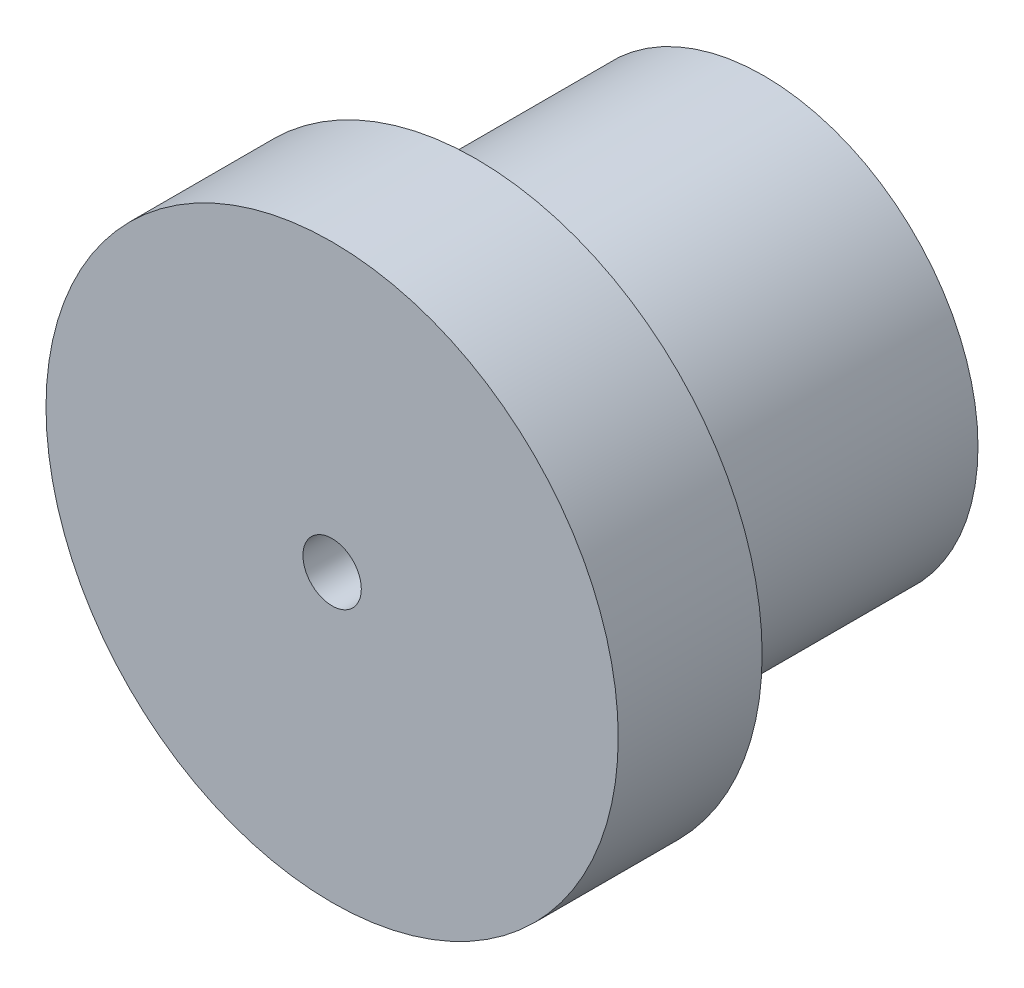
SolidWorks part; units mm, degrees
ref_plane "Front" through (0, 0, 0) normal (0, 0, 1) x (1, 0, 0)
ref_plane "Top" through (0, 0, 0) normal (0, 1, 0) x (1, 0, 0)
ref_plane "Right" through (0, 0, 0) normal (1, 0, 0) x (0, 0, -1)
sketch "Sketch1" plane through (0, 0, 0) normal (0, 0, 1) x (1, 0, 0)
  circle A0 centre (0, 0) radius 25.25
  circle A3 centre (0, 0) radius 25.4 construction
  dimension "D1" = 50.8
  dimension "D2" = 0.15
extrude "Boss-Extrude1" add sketch "Sketch1" against normal up to surface (12.7 mm away)
sketch "Sketch2" plane through (0, 0, -12.7) normal (0, 0, -1) x (-1, 0, 0)
  circle A0 centre (0, 0) radius 18.9
  circle A3 centre (0, 0) radius 19.05 construction
  dimension "D1" = 38.1
  dimension "D2" = 0.15
extrude "Boss-Extrude2" add sketch "Sketch2" along normal up to surface (25.4 mm away)
sketch "Sketch3" plane through (0, 0, -38.1) normal (0, 0, -1) x (-1, 0, 0)
  circle A0 centre (0, 0) radius 4.5
  dimension "D1" = 9
extrude "Cut-Extrude1" cut sketch "Sketch3" against normal blind 13
sketch "Sketch4" plane through (0, 0, 0) normal (0, 0, 1) x (1, 0, 0)
  line L0 (-2.24, 1.27) -> (2.24, 1.27)
  arc A0 (-2.24, 1.27) -> (2.24, 1.27) centre (0, 0) ccw
  arc A1 (2.24, 1.27) -> (-2.24, 1.27) centre (0, 0) ccw construction
  dimension "D1" = 5.15
  dimension "D2" = 4.48
extrude "Cut-Extrude2" cut sketch "Sketch4" against normal blind 20
sketch "Sketch5" plane through (0, 0, 0) normal (0, 0, 1) x (1, 0, 0)
  circle A0 centre (0, 0) radius 2.575
  dimension "D1" = 5.15
extrude "Cut-Extrude3" cut sketch "Sketch5" against normal blind 5
